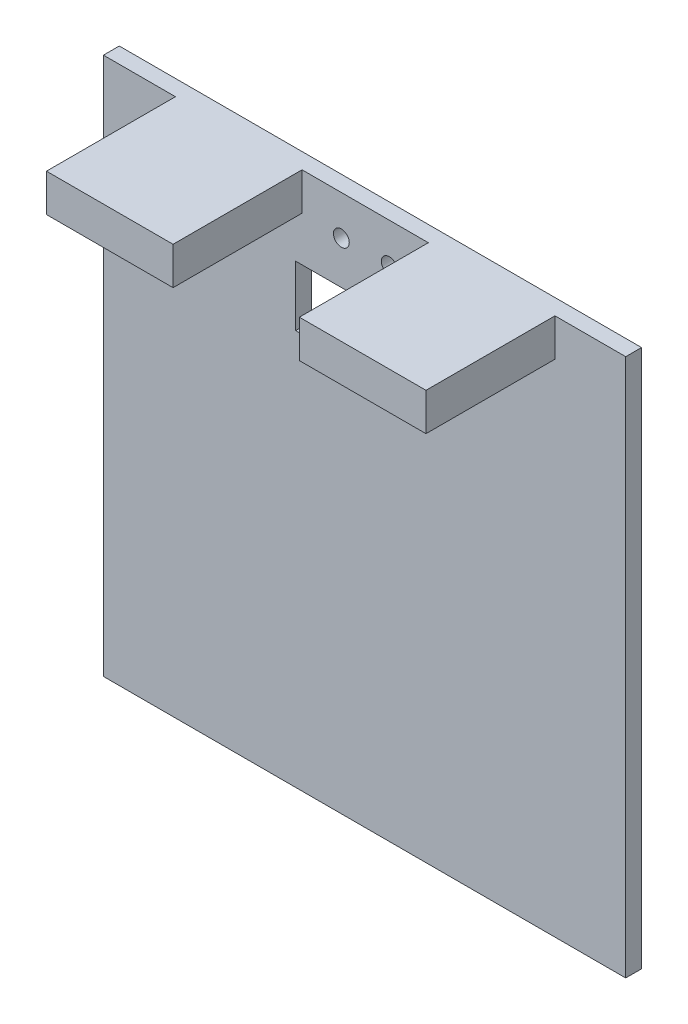
SolidWorks part; units mm, degrees
ref_plane "Front Plane" through (0, 0, 0) normal (0, 0, 1) x (1, 0, 0)
ref_plane "Top Plane" through (0, 0, 0) normal (0, 1, 0) x (1, 0, 0)
ref_plane "Right Plane" through (0, 0, 0) normal (1, 0, 0) x (0, 0, -1)
other "Graphic1"
other "object_1 (Open) -1"
ref_plane "Plane1" through (0, 0, 30) normal (0, 0, 1) x (1, 0, 0)
sketch "Sketch1" plane through (0, 0, 30) normal (0, 0, 1) x (1, 0, 0)
  line L1 (218.9409, 335.024) -> (284.9409, 335.024)
  line L2 (218.9409, 335.024) -> (218.9409, 267.024)
  line L3 (218.9409, 267.024) -> (284.9409, 267.024)
  line L4 (284.9409, 335.024) -> (284.9409, 267.024)
  line L5 (243.235, 324.6239) -> (261.035, 324.6239)
  line L6 (243.235, 324.6239) -> (243.235, 317.0239)
  line L7 (243.235, 317.0239) -> (261.035, 317.0239)
  line L8 (261.035, 324.6239) -> (261.035, 317.0239)
  circle A0 centre (249.0036, 330.0315) radius 1
  circle A1 centre (255.0553, 330.0315) radius 1
  dimension "D3" = 17.8
  dimension "D1" = 66
  dimension "D2" = 68
  dimension "D4" = 7.6
extrude "Boss-Extrude1" add sketch "Sketch1" along normal blind 2
sketch "Sketch2" plane through (0, 0, 32) normal (0, 0, 1) x (1, 0, 0)
  line L0 (284.9409, 335.024) -> (218.9409, 335.024) construction
  line L1 (244.038, 330.274) -> (228.038, 330.274)
  line L2 (244.038, 330.274) -> (244.038, 335.024)
  line L3 (244.038, 335.024) -> (228.038, 335.024)
  line L4 (228.038, 330.274) -> (228.038, 335.024)
  line L6 (276, 330.274) -> (260, 330.274)
  line L7 (276, 330.274) -> (276, 335.024)
  line L8 (276, 335.024) -> (260, 335.024)
  line L9 (260, 330.274) -> (260, 335.024)
  dimension "D1" = 16
  dimension "D2" = 4.75
  dimension "D3" = 16
  dimension "D4" = 4.75
extrude "Boss-Extrude2" add sketch "Sketch2" along normal blind 16.3
